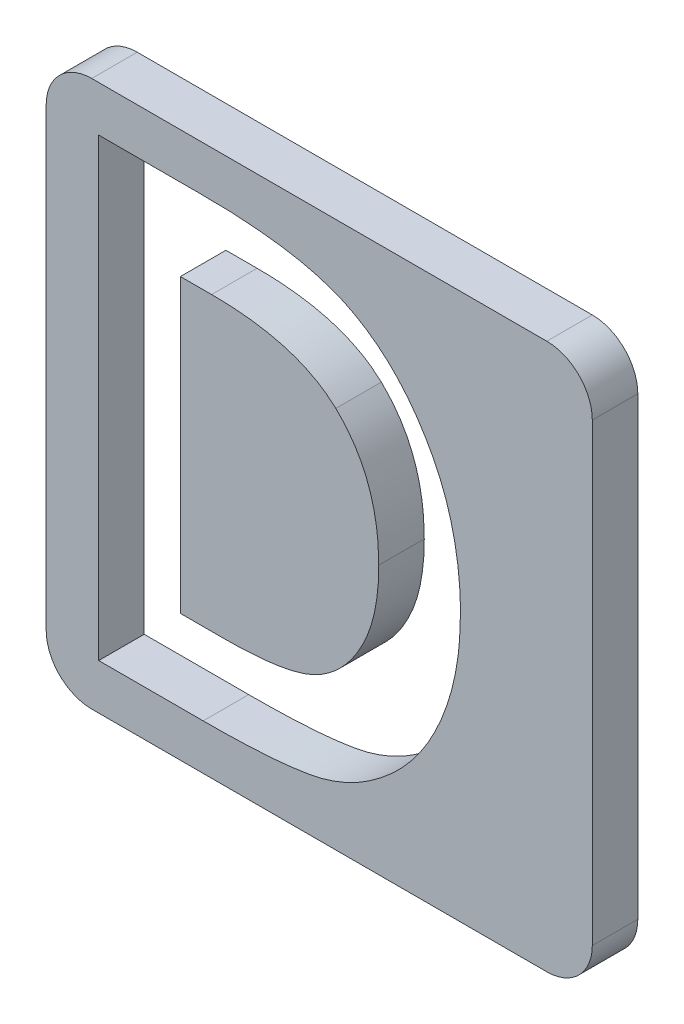
SolidWorks part; units mm, degrees
ref_plane "Front Plane" through (0, 0, 0) normal (0, 0, 1) x (1, 0, 0)
ref_plane "Top Plane" through (0, 0, 0) normal (0, 1, 0) x (1, 0, 0)
ref_plane "Right Plane" through (0, 0, 0) normal (1, 0, 0) x (0, 0, -1)
sketch "Sketch1" plane through (0, 0, 0) normal (0, 0, 1) x (1, 0, 0)
  line L1 (-50, 60) -> (50, 60)
  line L2 (-60, 50) -> (-60, -50)
  line L3 (-50, -60) -> (50, -60)
  line L4 (60, 50) -> (60, -50)
  line L5 (-60, 60) -> (60, -60) construction
  line L6 (-60, -60) -> (60, 60) construction
  arc A0 (-60, -50) -> (-50, -60) centre (-50, -50) ccw
  arc A1 (50, -60) -> (60, -50) centre (50, -50) ccw
  arc A2 (50, 60) -> (60, 50) centre (50, 50) cw
  arc A3 (-50, 60) -> (-60, 50) centre (-50, 50) ccw
  point P0 (0, 0)
  dimension "D3" = 10
  dimension "D1" = 120
  dimension "D2" = 120
extrude "Boss-Extrude1" add sketch "Sketch1" along normal blind 10 contours A3 L2 A0 L3 A1 L4 A2 L1
sketch "Sketch2" plane through (0, 0, 10) normal (0, 0, 1) x (1, 0, 0)
  line L0 (0, 0) -> (0, 40) construction
  line L1 (-50, 50) -> (50, 50) construction
  line L2 (-50, 50) -> (-50, -50) construction
  line L3 (-50, -50) -> (50, -50) construction
  line L4 (50, 50) -> (50, -50) construction
  line L5 (-50, 50) -> (50, -50) construction
  line L6 (-50, -50) -> (50, 50) construction
  line L7 (0, 40) -> (-40, 40) construction
  line L8 (-40, 40) -> (-40, 0) construction
  line L9 (-40, 0) -> (0, 0) construction
  line L11 (0, 20) -> (-20, 20) construction
  line L12 (-20, 40) -> (-20, 20) construction
  circle A0 centre (0, 40) radius 4 construction
  circle A1 centre (0, 20) radius 4 construction
  circle A2 centre (0, 0) radius 4 construction
  circle A3 centre (-20, 20) radius 4 construction
  circle A4 centre (-20, 40) radius 4 construction
  circle A5 centre (-40, 40) radius 4 construction
  circle A6 centre (0, 0) radius 4 construction
  circle A7 centre (20, 0) radius 4 construction
  circle A8 centre (40, 0) radius 4 construction
  circle A9 centre (40, 20) radius 4 construction
  circle A10 centre (40, 40) radius 4 construction
  circle A11 centre (20, 20) radius 4 construction
  circle A12 centre (0, 0) radius 4 construction
  circle A13 centre (0, -20) radius 4 construction
  circle A14 centre (0, -40) radius 4 construction
  circle A15 centre (20, -40) radius 4 construction
  circle A16 centre (40, -40) radius 4 construction
  circle A17 centre (20, -20) radius 4 construction
  circle A18 centre (0, 0) radius 4 construction
  circle A19 centre (-20, 0) radius 4 construction
  circle A20 centre (-40, 0) radius 4 construction
  circle A21 centre (-40, -20) radius 4 construction
  circle A22 centre (-40, -40) radius 4 construction
  circle A23 centre (-20, -20) radius 4 construction
  text T0 "D" font "Century Gothic" height 100
  point P0 (0, 0)
  point P55 (0, 0)
  dimension "D4" = 8
  dimension "D1" = 100
  dimension "D2" = 100
  dimension "D3" = 40
  dimension "D5" = 4
extrude "Cut-Extrude17" cut sketch "Sketch2" against normal blind 10
